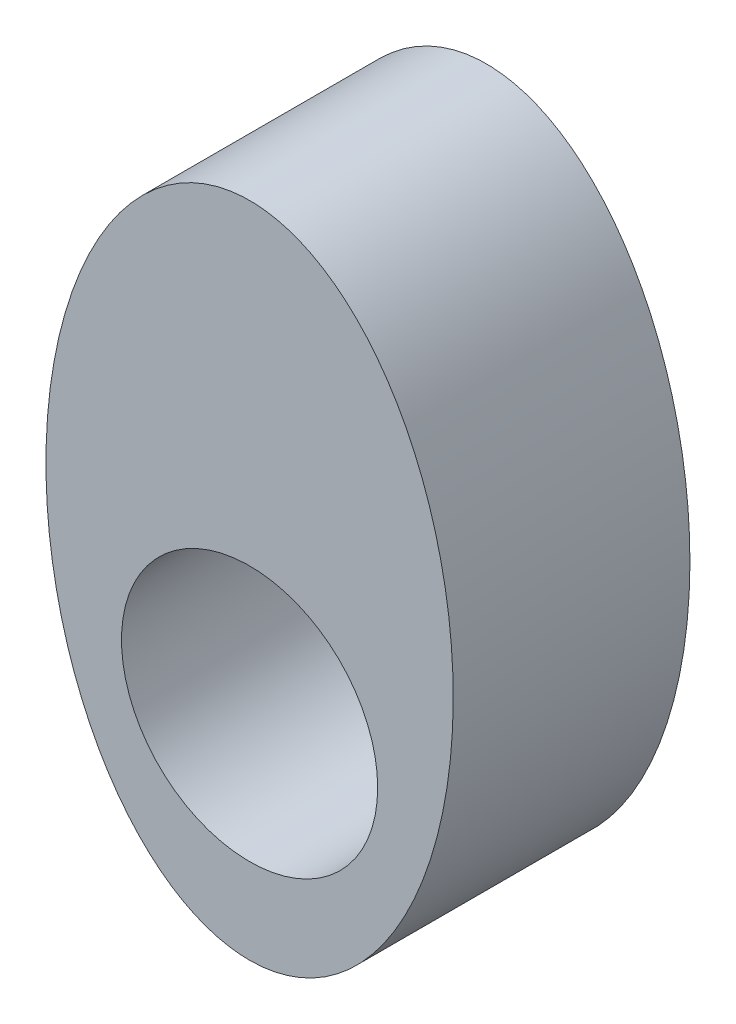
SolidWorks part; units mm, degrees
ref_plane "Front Plane" through (0, 0, 0) normal (0, 0, 1) x (1, 0, 0)
ref_plane "Top Plane" through (0, 0, 0) normal (0, 1, 0) x (1, 0, 0)
ref_plane "Right Plane" through (0, 0, 0) normal (1, 0, 0) x (0, 0, -1)
sketch "Sketch2" plane through (0, 0, 0) normal (0, 0, 1) x (1, 0, 0)
  circle A3 centre (0, 0) radius 4.7625
  ellipse E0 centre (0, 4.2953) end of major axis (0, -7.9375) minor radius 7.5711
  point P2 (0, 0)
  point P4 (0, 0)
  dimension "D1" = 9.525
  dimension "D2" = 7.9375
extrude "Boss-Extrude1" add sketch "Sketch2" along normal blind 8.8 contours E0 | A3
